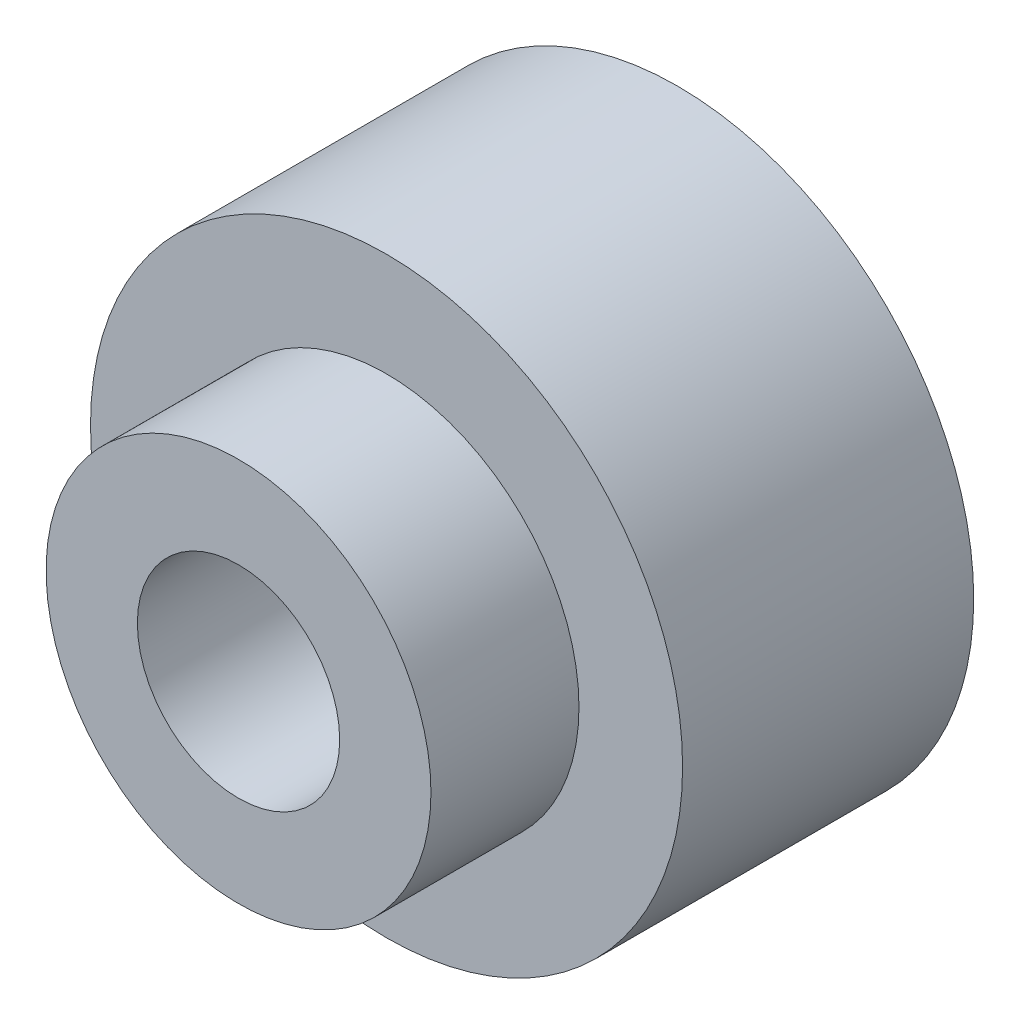
SolidWorks part; units mm, degrees
material "ABS PC"
ref_plane "Front Plane" through (0, 0, 0) normal (0, 0, 1) x (1, 0, 0)
ref_plane "Top Plane" through (0, 0, 0) normal (0, 1, 0) x (1, 0, 0)
ref_plane "Right Plane" through (0, 0, 0) normal (1, 0, 0) x (0, 0, -1)
sketch "Sketch1" plane through (0, 0, 0) normal (0, 0, 1) x (1, 0, 0)
  circle A0 centre (0, 0) radius 6
  circle A1 centre (0, 0) radius 2.05
  dimension "D1" = 12
  dimension "D2" = 4.1
extrude "Boss-Extrude1" add sketch "Sketch1" along normal blind 5.9
sketch "Sketch2" plane through (0, 0, 5.9) normal (0, 0, 1) x (1, 0, 0)
  circle A0 centre (0, 0) radius 2.05
  circle A1 centre (0, 0) radius 3.9
  dimension "D1" = 7.8
extrude "Boss-Extrude2" add sketch "Sketch2" along normal blind 3
